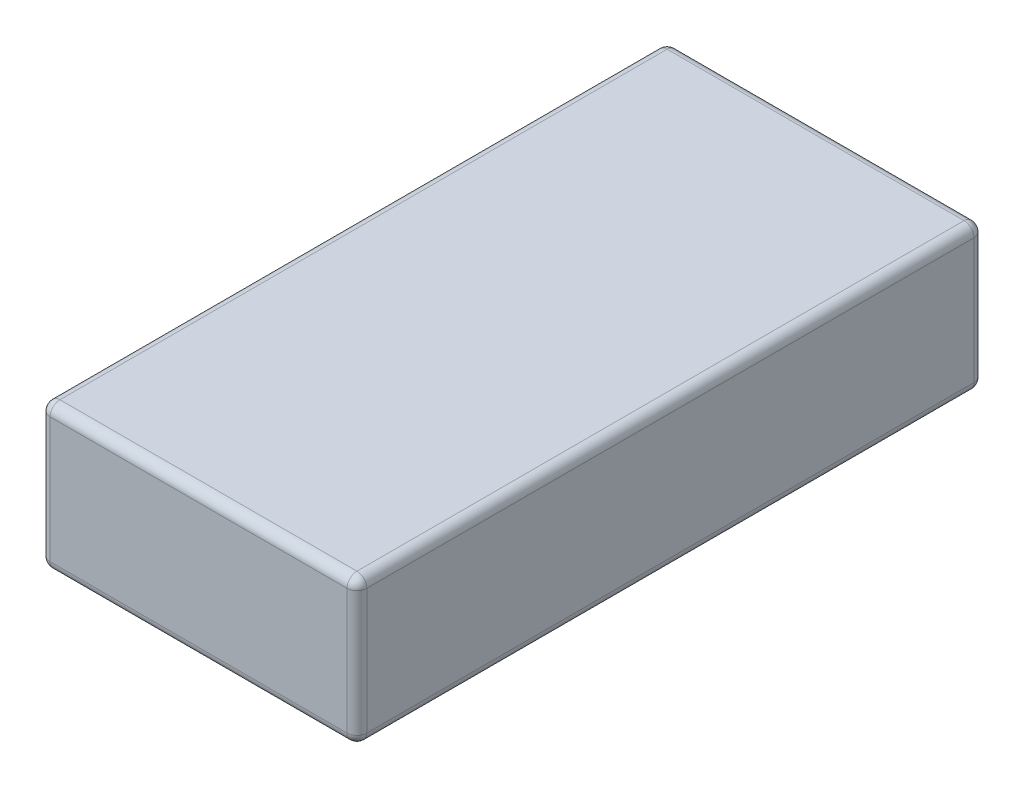
SolidWorks part; units mm, degrees
ref_plane "Спереди" through (0, 0, 0) normal (0, 0, 1) x (1, 0, 0)
ref_plane "Сверху" through (0, 0, 0) normal (0, 1, 0) x (1, 0, 0)
ref_plane "Справа" through (0, 0, 0) normal (1, 0, 0) x (0, 0, -1)
sketch "Эскиз1" plane through (0, 0, 0) normal (0, 0, 1) x (1, 0, 0)
  line L0 (0, 0) -> (48, 0)
  line L1 (48, 0) -> (48, 22)
  line L2 (48, 22) -> (0, 22)
  line L3 (0, 22) -> (0, 0)
  dimension "D1" = 22
  dimension "D2" = 48
extrude "Бобышка-Вытянуть1" add sketch "Эскиз1" against normal blind 95
fillet "Скругление1" radius 1.5 12 edges at (0, 0, -47.5) (0, 11, 0) (0, 11, -95) (24, 0, -95) (48, 11, 0) (48, 11, -95) (24, 22, -95) (0, 22, -47.5) (24, 0, 0) (24, 22, 0) (48, 0, -47.5) (48, 22, -47.5)
